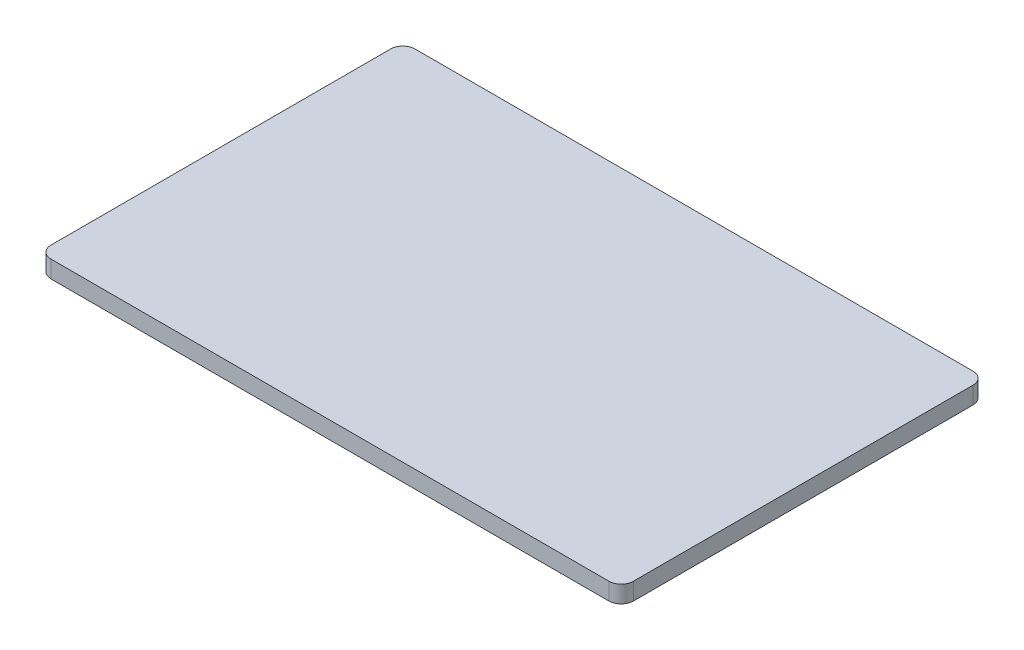
SolidWorks part; units mm, degrees
ref_plane "Front Plane" through (0, 0, 0) normal (0, 0, 1) x (1, 0, 0)
ref_plane "Top Plane" through (0, 0, 0) normal (0, 1, 0) x (1, 0, 0)
ref_plane "Right Plane" through (0, 0, 0) normal (1, 0, 0) x (0, 0, -1)
sketch "Sketch1" plane through (0, 0, 0) normal (0, 1, 0) x (1, 0, 0)
  line L1 (-152.4, -95.25) -> (152.4, -95.25)
  line L2 (-152.4, -95.25) -> (-152.4, 95.25)
  line L3 (-152.4, 95.25) -> (152.4, 95.25)
  line L4 (152.4, -95.25) -> (152.4, 95.25)
  line L5 (-152.4, -95.25) -> (152.4, 95.25) construction
  line L6 (-152.4, 95.25) -> (152.4, -95.25) construction
  point P0 (0, 0)
  dimension "D1" = 190.5
  dimension "D2" = 304.8
extrude "Boss-Extrude1" add sketch "Sketch1" along normal blind 13.589
chamfer "Chamfer1" distance 13.97 distance2 4.572 1 edges at (-152.4, 0, 0)
chamfer "Chamfer2" distance 13.97 distance2 4.572 1 edges at (6.985, 0, -95.25)
chamfer "Chamfer3" distance 13.97 distance2 4.572 1 edges at (152.4, 0, 6.985)
chamfer "Chamfer4" distance 13.97 distance2 4.572 1 edges at (0, 0, 95.25)
fillet "Fillet1" radius 6.35 4 edges at (-152.4, 9.0805, 95.25) (-152.4, 9.0805, -95.25) (152.4, 9.0805, -95.25) (152.4, 9.0805, 95.25)
fillet "Fillet3" radius 25.4 8 edges at (0, 0, 81.28) (144.4851, 1.9817, 87.3351) (138.43, 0, 0) (144.4851, 1.9817, -87.3351) (0, 0, -81.28) (-144.4851, 1.9817, -87.3351) (-138.43, 0, 0) (-144.4851, 1.9817, 87.3351)
